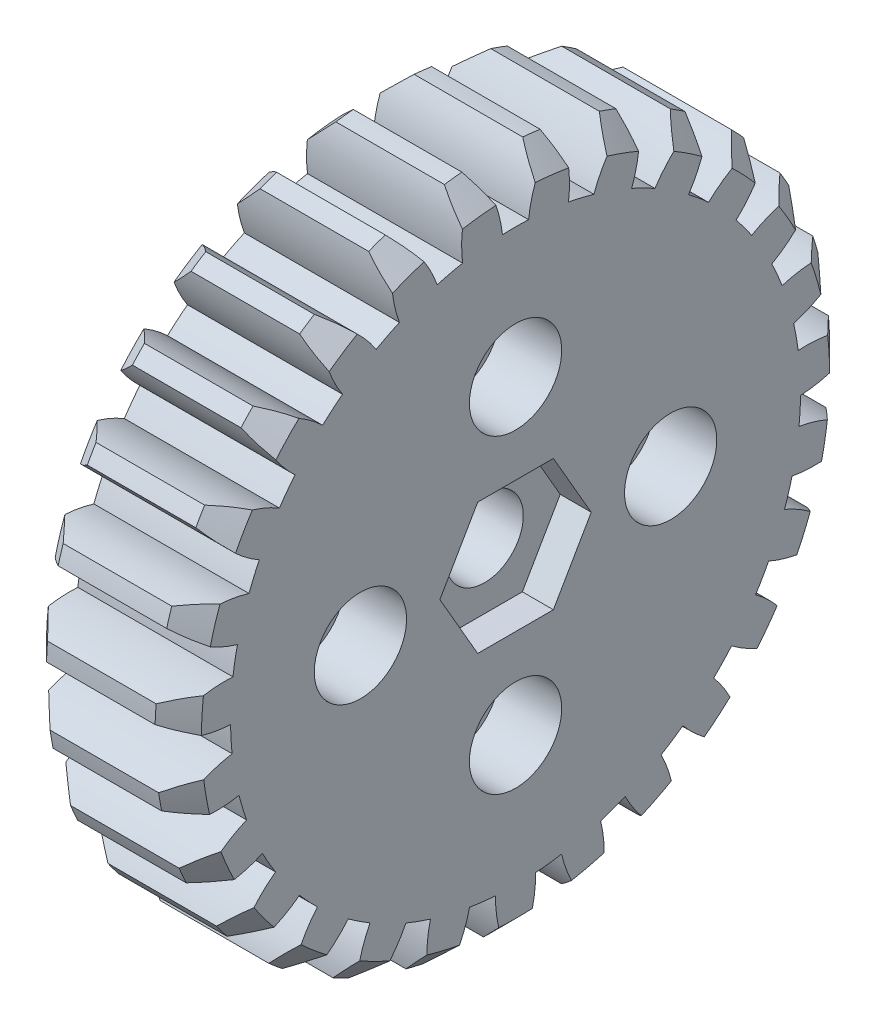
SolidWorks part; units mm, degrees
material "ABS"
ref_plane "Plane1" through (0, 0, 0) normal (0, 0, 1) x (1, 0, 0)
ref_plane "Plane2" through (0, 0, 0) normal (0, 1, 0) x (1, 0, 0)
ref_plane "Plane3" through (0, 0, 0) normal (1, 0, 0) x (0, 0, -1)
sketch "HoldingSke" plane through (0, 0, 0) normal (0, 1, 0) x (1, 0, 0)
  line L0 (0, 0) -> (0.594, -0.3027)
  line L1 (-15, 0) -> (100, 0) construction
  line L2 (0, 0) -> (-2.1039, 2.3779)
  line L3 (0, 0) -> (-11.863, 4.5341)
  line L4 (0, 0) -> (7.6947, 3.9207)
  line L5 (0, 0) -> (-46.8476, -17.4728)
  line L6 (0, 0) -> (-8.2896, -5.593)
  line L7 (-2.1039, 2.3779) -> (8.6586, 51.2059)
  line L8 (-76.2, 54.61) -> (-75.3, 54.61)
  line L9 (-67.7845, 28.3722) -> (-49.3413, 33.142)
  line L10 (-76.2, 71.12) -> (104.1128, 71.12)
  line L11 (0, 0) -> (-10, 0)
  line L12 (-76.2, 101.6) -> (-76.147, 101.6)
  line L13 (24.9733, 27.94) -> (52.9518, 28.4284)
  line L14 (24.9733, 27.94) -> (24.9743, 27.94)
  line L15 (24.9733, 27.94) -> (100.4006, 29.5858)
  line L16 (-63.627, -1.5) -> (-12.827, -1.5)
  circle A0 centre (0, 0) radius 2.5
  circle A1 centre (0, 0) radius 18.374
  circle A2 centre (0, 0) radius 37.5
  circle A3 centre (0, 0) radius 2.5
  dimension "MHD" = 36.748
  dimension "Hub_dia" = 75
  dimension "Bore" = 5
  dimension "MBD" = 5
  dimension "Num_teeth" = 27
  dimension "Pitch_radius" = 180.3128
  dimension "Pitch" = 0.6667
  dimension "Width" = 10
  dimension "Overall_len" = 50
  dimension "Show_teeth" = 27
  dimension "Thickness" = 10
  dimension "OAL" = 50.0001
  dimension "T_dim" = 0.9
  dimension "Ap" = 14.5
  dimension "H" = 19.05
  dimension "Backlash" = 0.053
  dimension "Addendum_fac" = 1
  dimension "Dedendum_fac" = 1.25
  dimension "Clearance_fac" = 0.25
  dimension "Dedendum_add" = 0.001
  dimension "Module" = 1.5
sketch "BasProSke" plane through (0, 0, 0) normal (0, 1, 0) x (1, 0, 0)
  line L0 (-10, 0) -> (60, 0) construction
  line L1 (0, 0) -> (0, 21.75)
  line L2 (0, 0) -> (10, 0)
  line L3 (10, 0) -> (10, 21.75)
  line L4 (10, 21.75) -> (0, 21.75)
  dimension "Diameter" = 43.5
  dimension "Thickness" = 10
revolve "Base-Revolve" add sketch "BasProSke" angle 360 about L0
sketch "TooCutSke" plane through (0, 0, 0) normal (1, 0, 0) x (0, 0, -1)
  line L1 (0, 0) -> (0, 107) construction
  line L2 (0, 0) -> (-1.2702, 20.2101) construction
  line L3 (0, 0) -> (-4.695, 40.1684) construction
  line L4 (-1.2702, 20.2101) -> (-2.3475, 20.0842) construction
  arc A0 (0.8415, 18.3547) -> (-0.8415, 18.3547) centre (0, 0) ccw
  arc A1 (1.9756, 21.6856) -> (-1.9756, 21.6856) centre (0, 0) ccw
  circle A2 centre (0, 0) radius 20.25 construction
  circle A3 centre (0, 0) radius 19.605 construction
  arc A4 (-0.8415, 18.3547) -> (-1.9756, 21.6856) centre (-8.8933, 17.4718) ccw
  arc A5 (1.9756, 21.6856) -> (0.8415, 18.3547) centre (8.8933, 17.4718) ccw
  dimension "Root_dia" = 36.748
  dimension "Overcut_dia" = 43.5508
  dimension "Pitch_dia" = 40.5
  dimension "Base_dia" = 39.21
  dimension "Flank_rad" = 8.1
  dimension "Half_ang" = 6.667
  dimension "Half_CT" = 1.0847
extrude "ToothCut" cut sketch "TooCutSke" along normal through all
fillet "Breaks" [suppressed] radius 0.03
fillet "RootFillets" [suppressed] radius 0.376
pattern_circular "TeethCuts" count 27 every 13.333 about axis through (-10, 0, 0) along (1, 0, 0) of "ToothCut", "RootFillets", "Breaks"
sketch "HubNeaOneSke" plane through (0, 0, 0) normal (-1, 0, 0) x (0, 0, 1)
  circle A0 centre (0, 0) radius 18.374
  dimension "Diameter" = 36.748
extrude "HubNearOne" [suppressed] add sketch "HubNeaOneSke" along normal blind 40.0001
sketch "HubNeaBotSke" plane through (0, 0, 0) normal (-1, 0, 0) x (0, 0, 1)
  circle A0 centre (0, 0) radius 18.374
  dimension "Diameter" = 36.748
extrude "HubNearBoth" [suppressed] add sketch "HubNeaBotSke" along normal blind 20
ref_plane "FarPln" through (10, 0, 0) normal (1, 0, 0) x (0, 0, -1)
sketch "HubFarSke" plane through (10, 0, 0) normal (1, 0, 0) x (0, 0, -1)
  circle A0 centre (0, 0) radius 18.374
  dimension "Diameter" = 36.748
extrude "HubFar" [suppressed] add sketch "HubFarSke" along normal blind 20
sketch "BorSke" plane through (0, 0, 0) normal (1, 0, 0) x (0, 0, -1)
  circle A0 centre (0, 0) radius 2.5
  dimension "Diameter" = 5
extrude "Bore" cut sketch "BorSke" along normal mid plane 100.0001
sketch "KeySke" plane through (0, 0, 0) normal (1, 0, 0) x (0, 0, -1)
  line L0 (-1, 0) -> (-1, 3.4)
  line L1 (-1, 3.4) -> (1, 3.4)
  line L2 (1, 3.4) -> (1, 0)
  line L3 (0, 0) -> (0, 34) construction
  line L4 (-1, 0) -> (1, 0)
  dimension "Offset" = 3.4
  dimension "Width" = 2
extrude "Keyway" [suppressed] cut sketch "KeySke" along normal mid plane 100.0001
pattern_circular "Keyway2" [suppressed] count 2 every 90 about axis through (-10, 0, 0) along (1, 0, 0)
sketch "Sketch1" plane through (0, 0, 0) normal (1, 0, 0) x (0, 0, -1)
  circle A0 centre (0, 0) radius 20.25
  dimension "D1" = 40.5
sketch "Sketch2" plane through (10, 0, -10) normal (-1, 0, 0) x (0, 0, 1)
  line L1 (14.8786, 0) -> (12.4393, 4.225)
  line L2 (12.4393, 4.225) -> (7.5607, 4.225)
  line L3 (7.5607, 4.225) -> (5.1214, 0)
  line L4 (5.1214, 0) -> (7.5607, -4.225)
  line L5 (7.5607, -4.225) -> (12.4393, -4.225)
  line L6 (12.4393, -4.225) -> (14.8786, 0)
  circle A0 centre (10, 0) radius 4.225 construction
  dimension "D1" = 8.45
extrude "Cut-Extrude1" cut sketch "Sketch2" along normal blind 2
sketch "Sketch4" plane through (10, 0, 0) normal (1, 0, 0) x (0, 0, -1)
  circle A0 centre (0, 0) radius 10 construction
  circle A1 centre (0, 10) radius 1.725
  circle A2 centre (10, 0) radius 1.725
  circle A3 centre (0, -10) radius 1.725
  circle A4 centre (-10, 0) radius 1.725
  dimension "D1" = 20
  dimension "D2" = 3.45
extrude "Cut-Extrude2" cut sketch "Sketch4" against normal through all
sketch "Sketch6" plane through (10, 0, 0) normal (-1, 0, 0) x (0, 0, 1)
  circle A0 centre (0, -10) radius 2.975
  circle A1 centre (10, 0) radius 2.975
  circle A2 centre (0, 10) radius 2.975
  circle A3 centre (-10, 0) radius 2.975
  dimension "D1" = 5.95
extrude "Cut-Extrude3" cut sketch "Sketch6" along normal blind 4
chamfer "Chamfer1" distance 1.5 angle 45 54 edges at (0, -21.1637, -5.0159) (0, -21.75, 0) (0, -21.1637, 5.0159) (0, -19.4365, 9.7614) (0, -19.4365, -9.7614) (0, -16.6615, -13.9806) (0, -12.9882, -17.4462) (0, -8.6147, -19.9712) (0, -3.7768, -21.4196) (0, 1.2647, -21.7132) (0, 6.238, -20.8363) (0, 10.875, -18.8361) (0, 14.9258, -15.8204) (0, 18.1719, -11.9518) (0, 20.4383, -7.4389) (0, 21.6029, -2.525) (0, 21.6029, 2.525) (0, 20.4383, 7.4389) (0, 18.1719, 11.9518) (0, 14.9258, 15.8204) (0, 10.875, 18.8361) (0, 6.238, 20.8363) (0, 1.2647, 21.7132) (0, -3.7768, 21.4196) (0, -8.6147, 19.9712) (0, -12.9882, 17.4462) (0, -16.6615, 13.9806) (10, -3.7768, -21.4196) (10, -8.6147, -19.9712) (10, -12.9882, -17.4462) (10, -16.6615, -13.9806) (10, -19.4365, -9.7614) (10, -21.1637, -5.0159) (10, -21.75, 0) (10, -21.1637, 5.0159) (10, -19.4365, 9.7614) (10, -16.6615, 13.9806) (10, -12.9882, 17.4462) (10, -8.6147, 19.9712) (10, -3.7768, 21.4196) (10, 1.2647, 21.7132) (10, 6.238, 20.8363) (10, 10.875, 18.8361) (10, 14.9258, 15.8204) (10, 18.1719, 11.9518) (10, 20.4383, 7.4389) (10, 21.6029, 2.525) (10, 21.6029, -2.525) (10, 20.4383, -7.4389) (10, 18.1719, -11.9518) (10, 14.9258, -15.8204) (10, 10.875, -18.8361) (10, 6.238, -20.8363) (10, 1.2647, -21.7132)
equation "' \"Module@HoldingSke\" = 6.35"
equation "' \"Num_teeth@HoldingSke\" = 12"
equation "' \"Ap@HoldingSke\" =  20"
equation "' \"Width@HoldingSke\" = 0.5 * 25.4"
equation "' \"Hub_dia@HoldingSke\"= 1 * 25.4"
equation "' \"Overall_len@HoldingSke\" = 1.0 * 25.4"
equation "' \"Bore@HoldingSke\" = 0.75 * 25.4"
equation "' \"T_dim@HoldingSke\" = 0.1 * 25.4"
equation "' \"Width@KeySke\" = 0.25 * 25.4"
equation "' \"Show_teeth@HoldingSke\" = 13"
equation "' \"Backlash@HoldingSke\" = 0.009 * 25.4"
equation "' \"Addendum_fac@HoldingSke\" = 1.0"
equation "' \"Dedendum_fac@HoldingSke\" = 1.25"
equation "' \"Dedendum_add@HoldingSke\" = 0.00005 * 25.4"
equation "' \"Clearance_fac@HoldingSke\" = 0.25"
equation "\"Pitch@HoldingSke\" = 1 / \"Module@HoldingSke\""
equation "\"Overcut_dia@TooCutSke\" = (\"Num_teeth@HoldingSke\" + 2 * \"Addendum_fac@HoldingSke\") / \"Pitch@HoldingSke\" + 0.002 * 25.4"
equation "\"Pitch_dia@TooCutSke\" = \"Num_teeth@HoldingSke\" / \"Pitch@HoldingSke\""
equation "\"Base_dia@TooCutSke\" = \"Num_teeth@HoldingSke\" / \"Pitch@HoldingSke\" * cos((\"Ap@HoldingSke\"  * 3.14159265 / 180))"
equation "\"Root_dia@TooCutSke\" = (\"Num_teeth@HoldingSke\" + 2) / \"Pitch@HoldingSke\" - 2 * (\"Addendum_fac@HoldingSke\" + \"Dedendum_fac@HoldingSke\") / \"Pitch@HoldingSke\" - \"Dedendum_add@HoldingSke\" * 2"
equation "\"Half_ang@TooCutSke\" = 180 / \"Num_teeth@HoldingSke\""
equation "\"Half_CT@TooCutSke\" = \"Num_teeth@HoldingSke\" / \"Pitch@HoldingSke\" * sin((3.14159265 / 2 / \"Num_teeth@HoldingSke\")) / 2 - 7 * \"Backlash@HoldingSke\" / 4"
equation "\"Flank_rad@TooCutSke\" = \"Num_teeth@HoldingSke\" / \"Pitch@HoldingSke\" / 5"
equation "\"Radius@RootFillets\" = \"Clearance_fac@HoldingSke\" / \"Pitch@HoldingSke\" + \"Dedendum_add@HoldingSke\""
equation "\"Break_rad@Breaks\" = 0.02 / \"Pitch@HoldingSke\""
equation "\"Thickness@HoldingSke\" = \"Width@HoldingSke\""
equation "\"OAL@HoldingSke\" = \"Thickness@HoldingSke\""
equation "\"MHD@HoldingSke\" = (\"Num_teeth@HoldingSke\" + 2) / \"Pitch@HoldingSke\" - 2 * (\"Addendum_fac@HoldingSke\" + \"Dedendum_fac@HoldingSke\")  / \"Pitch@HoldingSke\" - \"Dedendum_add@HoldingSke\" * 2"
equation "\"MBD@HoldingSke\" = (\"Num_teeth@HoldingSke\" + 2) / \"Pitch@HoldingSke\" - 2 * (\"Addendum_fac@HoldingSke\" + \"Dedendum_fac@HoldingSke\")  / \"Pitch@HoldingSke\" - \"Dedendum_add@HoldingSke\" * 2 - 0.002 * 25.4"
equation "\"MHD@HoldingSke\" = ((sgn( \"MHD@HoldingSke\" - \"Hub_dia@HoldingSke\" )-1)*( \"MHD@HoldingSke\" - \"Hub_dia@HoldingSke\" ))/-2+ \"Hub_dia@HoldingSke\""
equation "\"MBD@HoldingSke\" = ((sgn( \"MBD@HoldingSke\" - \"Bore@HoldingSke\" )-1)*( \"MBD@HoldingSke\" - \"Bore@HoldingSke\" ))/-2+ \"Bore@HoldingSke\""
equation "\"OAL@HoldingSke\" = ((sgn( \"OAL@HoldingSke\" - \"Overall_len@HoldingSke\" )+1)*( \"OAL@HoldingSke\" - \"Overall_len@HoldingSke\" ))/2 + \"Overall_len@HoldingSke\" + 0.000002 * 25.4"
equation "\"Num_teeth@TeethCuts\" = int( \"Show_teeth@HoldingSke\" ) + 1"
equation "\"Num_teeth@TeethCuts\" = ((sgn( \"Num_teeth@TeethCuts\" - \"Num_teeth@HoldingSke\" )-1)*( \"Num_teeth@TeethCuts\" - \"Num_teeth@HoldingSke\" ))/-2+ \"Num_teeth@HoldingSke\""
equation "\"Num_teeth@TeethCuts\" = ((sgn( \"Num_teeth@TeethCuts\" - 2.0)+1)*( \"Num_teeth@TeethCuts\" - 2.0))/2 +2.0"
equation "\"Angle@TeethCuts\" = 360.0 / \"Num_teeth@HoldingSke\""
equation "\"Diameter@BasProSke\" = (\"Num_teeth@HoldingSke\" + 2 * \"Addendum_fac@HoldingSke\") / \"Pitch@HoldingSke\""
equation "\"Thickness@BasProSke\"  = \"Thickness@HoldingSke\""
equation "' \"Fillet_rad@BasProSke\" =  \"Thickness@HoldingSke\" * 0.05"
equation "\"MHD@HoldingSke\" = ((sgn( \"MHD@HoldingSke\" - \"Root_dia@TooCutSke\" )-1)*( \"MHD@HoldingSke\" - \"Root_dia@TooCutSke\" ))/-2+ \"Root_dia@TooCutSke\""
equation "\"Diameter@HubNeaOneSke\" = \"MHD@HoldingSke\""
equation "\"Length@HubNearOne\" = \"OAL@HoldingSke\" - \"Thickness@BasProSke\""
equation "\"Diameter@HubNeaBotSke\" = \"MHD@HoldingSke\""
equation "\"Length@HubNearBoth\" = ( \"OAL@HoldingSke\" - \"Thickness@BasProSke\" ) / 2.0"
equation "\"Thickness@FarPln\" = \"Thickness@BasProSke\""
equation "\"Diameter@HubFarSke\" = \"MHD@HoldingSke\""
equation "\"Length@HubFar\" = ( \"OAL@HoldingSke\" - \"Thickness@BasProSke\" ) / 2.0"
equation "\"Diameter@BorSke\" = \"MBD@HoldingSke\""
equation "\"D1@Bore\" = \"OAL@HoldingSke\" * 2.0"
equation "\"D1@Keyway\" = \"OAL@HoldingSke\" * 2.0"
equation "\"Offset@KeySke\" = \"T_dim@HoldingSke\" + \"MBD@HoldingSke\" / 2.0"
equation "\"D1@Sketch2\"=8.00mm+\"print_free@Parameters@Parameters.SLDPRT\""
equation "\"D2@Sketch4\"=3.00mm+\"print_free@Parameters@Parameters.SLDPRT\""
equation "\"D1@Sketch6\"=5.50mm+\"print_free@Parameters@Parameters.SLDPRT\""
